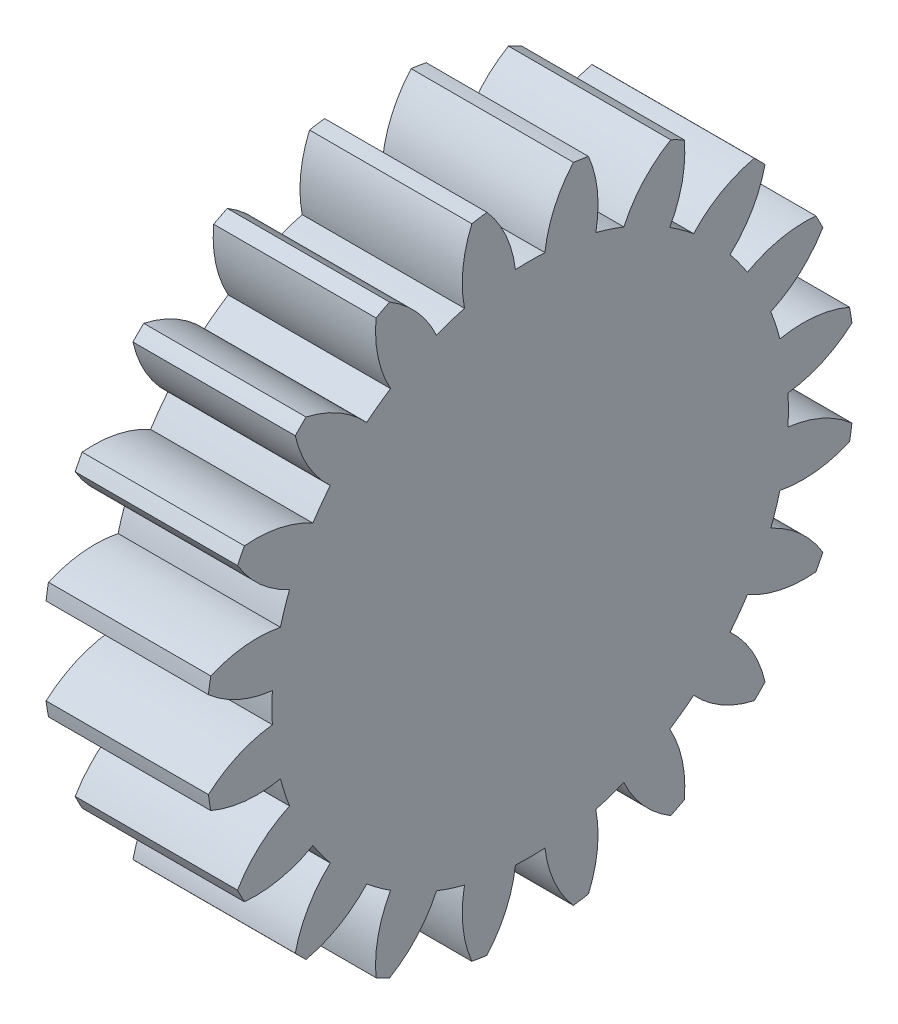
SolidWorks part; units mm, degrees
material "ﾎﾟﾘｵｷｼﾒﾁﾚﾝ(POM)ｱｾﾀｰﾙ共重合体"
ref_plane "Plane1" through (0, 0, 0) normal (0, 0, 1) x (1, 0, 0)
ref_plane "Plane2" through (0, 0, 0) normal (0, 1, 0) x (1, 0, 0)
ref_plane "Plane3" through (0, 0, 0) normal (1, 0, 0) x (0, 0, -1)
other "Configuration Table"
sketch "HoldingSke" plane through (0, 0, 0) normal (0, 1, 0) x (1, 0, 0)
  line L0 (0, 0) -> (0.9397, -0.342)
  line L1 (-15, 0) -> (100, 0) construction
  line L2 (0, 0) -> (-2.1039, 2.3779)
  line L3 (0, 0) -> (-11.863, 4.5341)
  line L4 (0, 0) -> (8.1152, 2.9537)
  line L5 (0, 0) -> (-46.8476, -17.4728)
  line L6 (0, 0) -> (-4.5593, -3.0762)
  line L7 (-2.1039, 2.3779) -> (8.6586, 51.2059)
  line L8 (-76.2, 54.61) -> (-75.2, 54.61)
  line L9 (-71.009, 38.7566) -> (-53.1078, 45.2721)
  line L10 (-76.2, 71.12) -> (104.1128, 71.12)
  line L11 (0, 0) -> (-5.5, 0)
  line L12 (-76.2, 101.6) -> (-76.162, 101.6)
  line L13 (24.9733, 27.94) -> (52.9518, 28.4284)
  line L14 (24.9733, 27.94) -> (24.9743, 27.94)
  line L15 (24.9733, 27.94) -> (100.4006, 29.5858)
  line L16 (-63.627, -1) -> (-12.827, -1)
  circle A0 centre (0, 0) radius 3
  circle A1 centre (0, 0) radius 8.749
  circle A2 centre (0, 0) radius 37.5
  circle A3 centre (0, 0) radius 3
  dimension "MHD" = 17.498
  dimension "Hub_dia" = 75
  dimension "Bore" = 6
  dimension "MBD" = 6
  dimension "Num_teeth" = 20
  dimension "Pitch" = 1
  dimension "Overall_len" = 50
  dimension "Show_teeth" = 20
  dimension "Thickness" = 5.5
  dimension "OAL" = 50.0001
  dimension "T_dim" = 1
  dimension "Ap" = 20
  dimension "H" = 19.05
  dimension "Pitch_radius" = 180.3128
  dimension "Width" = 5.5
  dimension "Backlash" = 0.038
  dimension "Addendum_fac" = 1
  dimension "Dedendum_fac" = 1.25
  dimension "Clearance_fac" = 0.25
  dimension "Dedendum_add" = 0.001
  dimension "Module" = 1
sketch "BasProSke" plane through (0, 0, 0) normal (0, 1, 0) x (1, 0, 0)
  line L0 (-10, 0) -> (60, 0) construction
  line L1 (0, 0) -> (0, 11)
  line L2 (0, 0) -> (5.5, 0)
  line L3 (5.5, 0) -> (5.5, 11)
  line L4 (5.5, 11) -> (0, 11)
  dimension "Thickness" = 5.5
  dimension "Diameter" = 22
revolve "Base-Revolve" add sketch "BasProSke" angle 360 about L0
sketch "TooCutSke" plane through (0, 0, 0) normal (1, 0, 0) x (0, 0, -1)
  line L1 (0, 0) -> (0, 107) construction
  line L2 (0, 0) -> (-0.8511, 9.9637) construction
  line L3 (0, 0) -> (-3.1206, 19.7028) construction
  line L4 (-0.8511, 9.9637) -> (-1.5603, 9.8514) construction
  arc A0 (0.4999, 8.7347) -> (-0.4999, 8.7347) centre (0, 0) ccw
  arc A1 (1.4852, 10.9249) -> (-1.4852, 10.9249) centre (0, 0) ccw
  circle A2 centre (0, 0) radius 10 construction
  circle A3 centre (0, 0) radius 9.3969 construction
  arc A4 (-0.4999, 8.7347) -> (-1.4852, 10.9249) centre (-4.4722, 8.2645) ccw
  arc A5 (1.4852, 10.9249) -> (0.4999, 8.7347) centre (4.4722, 8.2645) ccw
  dimension "Root_dia" = 17.498
  dimension "Overcut_dia" = 22.0508
  dimension "Pitch_dia" = 20
  dimension "Base_dia" = 18.7939
  dimension "Flank_rad" = 4
  dimension "Half_ang" = 9
  dimension "Half_CT" = 0.7181
extrude "ToothCut" cut sketch "TooCutSke" along normal through all
fillet "Breaks" [suppressed] radius 0.02
fillet "RootFillets" [suppressed] radius 0.251
pattern_circular "TeethCuts" count 20 every 18 about axis through (-10, 0, 0) along (1, 0, 0) of "ToothCut", "RootFillets", "Breaks"
sketch "HubNeaOneSke" plane through (0, 0, 0) normal (-1, 0, 0) x (0, 0, 1)
  circle A0 centre (0, 0) radius 8.749
  dimension "Diameter" = 17.498
extrude "HubNearOne" [suppressed] add sketch "HubNeaOneSke" along normal blind 44.5001
sketch "HubNeaBotSke" plane through (0, 0, 0) normal (-1, 0, 0) x (0, 0, 1)
  circle A0 centre (0, 0) radius 8.749
  dimension "Diameter" = 17.498
extrude "HubNearBoth" [suppressed] add sketch "HubNeaBotSke" along normal blind 22.25
ref_plane "FarPln" through (5.5, 0, 0) normal (1, 0, 0) x (0, 0, -1)
sketch "HubFarSke" plane through (5.5, 0, 0) normal (1, 0, 0) x (0, 0, -1)
  circle A0 centre (0, 0) radius 8.749
  dimension "Diameter" = 17.498
extrude "HubFar" [suppressed] add sketch "HubFarSke" along normal blind 22.25
sketch "BorSke" plane through (0, 0, 0) normal (1, 0, 0) x (0, 0, -1)
  circle A0 centre (0, 0) radius 3
  dimension "Diameter" = 6
extrude "Bore" cut sketch "BorSke" along normal mid plane 100.0001
sketch "KeySke" plane through (0, 0, 0) normal (1, 0, 0) x (0, 0, -1)
  line L0 (-1, 0) -> (-1, 4)
  line L1 (-1, 4) -> (1, 4)
  line L2 (1, 4) -> (1, 0)
  line L3 (0, 0) -> (0, 34) construction
  line L4 (-1, 0) -> (1, 0)
  dimension "Offset" = 4
  dimension "Width" = 2
extrude "Keyway" [suppressed] cut sketch "KeySke" along normal mid plane 100.0001
pattern_circular "Keyway2" [suppressed] count 2 every 90 about axis through (-10, 0, 0) along (1, 0, 0)
sketch "ｽｹｯﾁ1" plane through (0, 0, 0) normal (-1, 0, 0) x (0, 0, 1)
  circle A0 centre (0, 0) radius 3
  circle A1 centre (0, 0) radius 3 construction
extrude "ﾎﾞｽ - 押し出し1" add sketch "ｽｹｯﾁ1" against normal up to surface (5.5 mm away) contours A0 up to face at (5.5, 0, 3)
equation "' \"Module@HoldingSke\" = 6.35"
equation "' \"Num_teeth@HoldingSke\" = 12"
equation "' \"Ap@HoldingSke\" =  20"
equation "' \"Ap@HoldingSke\" = 20"
equation "' \"Width@HoldingSke\" = 0.5 * 25.4"
equation "' \"Hub_dia@HoldingSke\"= 1 * 25.4"
equation "' \"Hub_dia@HoldingSke\" = 1 * 25.4"
equation "' \"Overall_len@HoldingSke\" = 1.0 * 25.4"
equation "' \"Bore@HoldingSke\" = 0.75 * 25.4"
equation "' \"T_dim@HoldingSke\" = 0.1 * 25.4"
equation "' \"Width@KeySke\" = 0.25 * 25.4"
equation "' \"Show_teeth@HoldingSke\" = 13"
equation "' \"Backlash@HoldingSke\" = 0.009 * 25.4"
equation "' \"Addendum_fac@HoldingSke\" = 1.0"
equation "' \"Dedendum_fac@HoldingSke\" = 1.25"
equation "' \"Dedendum_add@HoldingSke\" = 0.00005 * 25.4"
equation "' \"Clearance_fac@HoldingSke\" = 0.25"
equation "\"Pitch@HoldingSke\" = 1 / \"Module@HoldingSke\""
equation "\"Overcut_dia@TooCutSke\" = (\"Num_teeth@HoldingSke\" + 2 * \"Addendum_fac@HoldingSke\") / \"Pitch@HoldingSke\" + 0.002 * 25.4"
equation "\"Pitch_dia@TooCutSke\" = \"Num_teeth@HoldingSke\" / \"Pitch@HoldingSke\""
equation "\"Base_dia@TooCutSke\" = \"Num_teeth@HoldingSke\" / \"Pitch@HoldingSke\" * cos((\"Ap@HoldingSke\"  * 3.14159265 / 180))"
equation "\"Root_dia@TooCutSke\" = (\"Num_teeth@HoldingSke\" + 2) / \"Pitch@HoldingSke\" - 2 * (\"Addendum_fac@HoldingSke\" + \"Dedendum_fac@HoldingSke\") / \"Pitch@HoldingSke\" - \"Dedendum_add@HoldingSke\" * 2"
equation "\"Half_ang@TooCutSke\" = 180 / \"Num_teeth@HoldingSke\""
equation "\"Half_CT@TooCutSke\" = \"Num_teeth@HoldingSke\" / \"Pitch@HoldingSke\" * sin((3.14159265 / 2 / \"Num_teeth@HoldingSke\")) / 2 - 7 * \"Backlash@HoldingSke\" / 4"
equation "\"Flank_rad@TooCutSke\" = \"Num_teeth@HoldingSke\" / \"Pitch@HoldingSke\" / 5"
equation "\"Radius@RootFillets\" = \"Clearance_fac@HoldingSke\" / \"Pitch@HoldingSke\" + \"Dedendum_add@HoldingSke\""
equation "\"Break_rad@Breaks\" = 0.02 / \"Pitch@HoldingSke\""
equation "\"Thickness@HoldingSke\" = \"Width@HoldingSke\""
equation "\"OAL@HoldingSke\" = \"Thickness@HoldingSke\""
equation "\"MHD@HoldingSke\" = (\"Num_teeth@HoldingSke\" + 2) / \"Pitch@HoldingSke\" - 2 * (\"Addendum_fac@HoldingSke\" + \"Dedendum_fac@HoldingSke\")  / \"Pitch@HoldingSke\" - \"Dedendum_add@HoldingSke\" * 2"
equation "\"MBD@HoldingSke\" = (\"Num_teeth@HoldingSke\" + 2) / \"Pitch@HoldingSke\" - 2 * (\"Addendum_fac@HoldingSke\" + \"Dedendum_fac@HoldingSke\")  / \"Pitch@HoldingSke\" - \"Dedendum_add@HoldingSke\" * 2 - 0.002 * 25.4"
equation "\"MHD@HoldingSke\" = ((sgn( \"MHD@HoldingSke\" - \"Hub_dia@HoldingSke\" )-1)*( \"MHD@HoldingSke\" - \"Hub_dia@HoldingSke\" ))/-2+ \"Hub_dia@HoldingSke\""
equation "\"MBD@HoldingSke\" = ((sgn( \"MBD@HoldingSke\" - \"Bore@HoldingSke\" )-1)*( \"MBD@HoldingSke\" - \"Bore@HoldingSke\" ))/-2+ \"Bore@HoldingSke\""
equation "\"OAL@HoldingSke\" = ((sgn( \"OAL@HoldingSke\" - \"Overall_len@HoldingSke\" )+1)*( \"OAL@HoldingSke\" - \"Overall_len@HoldingSke\" ))/2 + \"Overall_len@HoldingSke\" + 0.000002 * 25.4"
equation "\"Num_teeth@TeethCuts\" = int( \"Show_teeth@HoldingSke\" ) + 1"
equation "\"Num_teeth@TeethCuts\" = ((sgn( \"Num_teeth@TeethCuts\" - \"Num_teeth@HoldingSke\" )-1)*( \"Num_teeth@TeethCuts\" - \"Num_teeth@HoldingSke\" ))/-2+ \"Num_teeth@HoldingSke\""
equation "\"Num_teeth@TeethCuts\" = ((sgn( \"Num_teeth@TeethCuts\" - 2.0)+1)*( \"Num_teeth@TeethCuts\" - 2.0))/2 +2.0"
equation "\"Angle@TeethCuts\" = 360.0 / \"Num_teeth@HoldingSke\""
equation "\"Diameter@BasProSke\" = (\"Num_teeth@HoldingSke\" + 2 * \"Addendum_fac@HoldingSke\") / \"Pitch@HoldingSke\""
equation "\"Thickness@BasProSke\"  = \"Thickness@HoldingSke\""
equation "' \"Fillet_rad@BasProSke\" =  \"Thickness@HoldingSke\" * 0.05"
equation "' \"Fillet_rad@BasProSke\" = \"Thickness@HoldingSke\" * 0.05"
equation "\"MHD@HoldingSke\" = ((sgn( \"MHD@HoldingSke\" - \"Root_dia@TooCutSke\" )-1)*( \"MHD@HoldingSke\" - \"Root_dia@TooCutSke\" ))/-2+ \"Root_dia@TooCutSke\""
equation "\"Diameter@HubNeaOneSke\" = \"MHD@HoldingSke\""
equation "\"Length@HubNearOne\" = \"OAL@HoldingSke\" - \"Thickness@BasProSke\""
equation "\"Diameter@HubNeaBotSke\" = \"MHD@HoldingSke\""
equation "\"Length@HubNearBoth\" = ( \"OAL@HoldingSke\" - \"Thickness@BasProSke\" ) / 2.0"
equation "\"Thickness@FarPln\" = \"Thickness@BasProSke\""
equation "\"Diameter@HubFarSke\" = \"MHD@HoldingSke\""
equation "\"Length@HubFar\" = ( \"OAL@HoldingSke\" - \"Thickness@BasProSke\" ) / 2.0"
equation "\"Diameter@BorSke\" = \"MBD@HoldingSke\""
equation "\"D1@Bore\" = \"OAL@HoldingSke\" * 2.0"
equation "\"D1@Keyway\" = \"OAL@HoldingSke\" * 2.0"
equation "\"Offset@KeySke\" = \"T_dim@HoldingSke\" + \"MBD@HoldingSke\" / 2.0"
